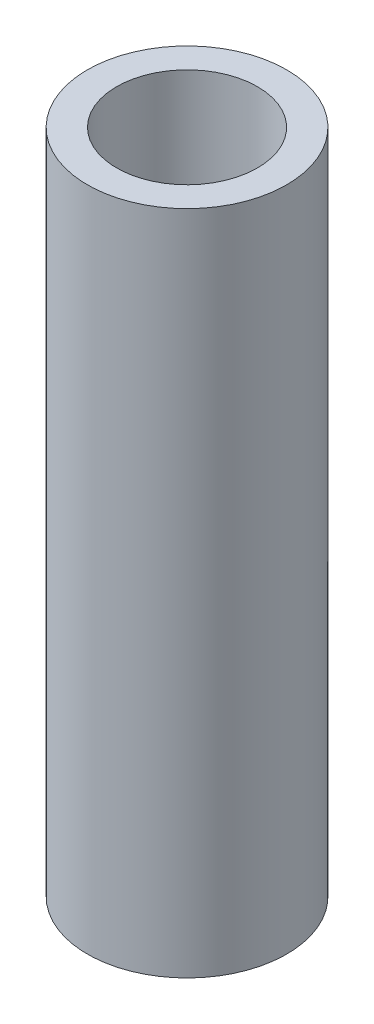
SolidWorks part; units mm, degrees
material "Rubber"
ref_plane "Front Plane" through (0, 0, 0) normal (0, 0, 1) x (1, 0, 0)
ref_plane "Top Plane" through (0, 0, 0) normal (0, 1, 0) x (1, 0, 0)
ref_plane "Right Plane" through (0, 0, 0) normal (1, 0, 0) x (0, 0, -1)
sketch "Sketch1" plane through (0, 0, 0) normal (0, 1, 0) x (1, 0, 0)
  circle A0 centre (0, 0) radius 6.025
extrude "Extrude-Thin1" add sketch "Sketch1" along normal blind 57 thin
